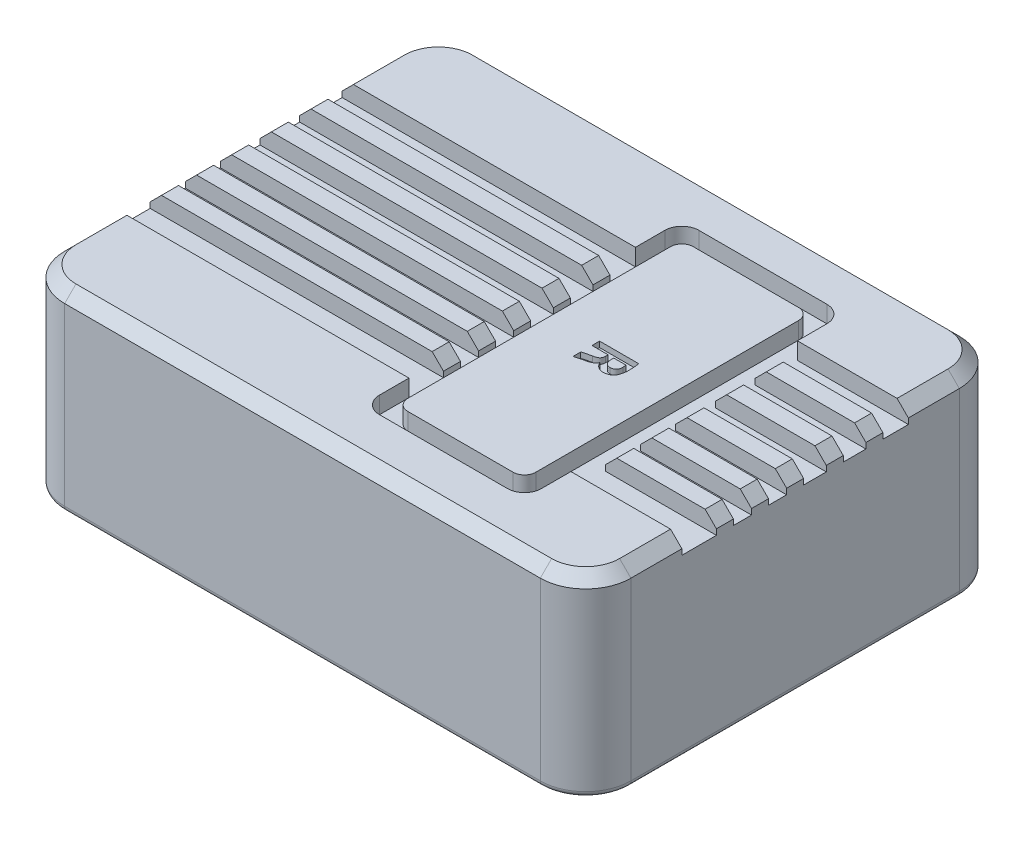
SolidWorks part; units mm, degrees
material "尼龙 101"
ref_plane "前视基准面" through (0, 0, 0) normal (0, 0, 1) x (1, 0, 0)
ref_plane "上视基准面" through (0, 0, 0) normal (0, 1, 0) x (1, 0, 0)
ref_plane "右视基准面" through (0, 0, 0) normal (1, 0, 0) x (0, 0, -1)
sketch "草图1" plane through (0, 0, 0) normal (0, 1, 0) x (1, 0, 0)
  line L1 (-21, 18.5) -> (21, 18.5)
  line L2 (-25, 14.5) -> (-25, -14.5)
  line L3 (-21, -18.5) -> (21, -18.5)
  line L4 (25, 14.5) -> (25, -14.5)
  line L5 (-25, 18.5) -> (25, -18.5) construction
  line L6 (-25, -18.5) -> (25, 18.5) construction
  arc A0 (-21, 18.5) -> (-25, 14.5) centre (-21, 14.5) ccw
  arc A1 (-25, -14.5) -> (-21, -18.5) centre (-21, -14.5) ccw
  arc A2 (21, -18.5) -> (25, -14.5) centre (21, -14.5) ccw
  arc A3 (21, 18.5) -> (25, 14.5) centre (21, 14.5) cw
  point P0 (0, 0)
  dimension "D3" = 4
  dimension "D1" = 50
  dimension "D2" = 37
extrude "凸台-拉伸1" add sketch "草图1" along normal blind 17
sketch "草图3" plane through (0, 17, 0) normal (0, 1, 0) x (1, 0, 0)
  line L0 (25, -14.5) -> (25, 14.5) construction
  line L1 (2.4, 14.1) -> (13.7, 14.1)
  line L2 (0.9, 12.6) -> (0.9, -12.6)
  line L3 (2.4, -14.1) -> (13.7, -14.1)
  line L4 (15.2, 12.6) -> (15.2, -12.6)
  line L5 (0.9, 14.1) -> (15.2, -14.1) construction
  line L6 (0.9, -14.1) -> (15.2, 14.1) construction
  line L7 (0, 0) -> (8.05, 0) construction
  line L9 (-25, 10) -> (25, 10)
  line L10 (-25, 10) -> (-25, -10)
  line L11 (-25, -10) -> (25, -10)
  line L12 (25, 10) -> (25, -10)
  line L13 (-25, 10) -> (25, -10) construction
  line L14 (-25, -10) -> (25, 10) construction
  arc A0 (0.9, -12.6) -> (2.4, -14.1) centre (2.4, -12.6) ccw
  arc A1 (13.7, -14.1) -> (15.2, -12.6) centre (13.7, -12.6) ccw
  arc A2 (13.7, 14.1) -> (15.2, 12.6) centre (13.7, 12.6) cw
  arc A3 (2.4, 14.1) -> (0.9, 12.6) centre (2.4, 12.6) ccw
  point P0 (8.05, 0)
  line M12 (-25, 14.5) -> (-25, -14.5)
  line M16 (25, -14.5) -> (25, 14.5)
  dimension "D1" = 1.5
  dimension "D2" = 14.3
  dimension "D3" = 9.8
  dimension "D4" = 28.2
  dimension "D5" = 20
extrude "切除-拉伸1" cut sketch "草图3" against normal blind 1.5 contours L4 L11 L9 M16 | L2 L11 L4 L9 | L1 A3 L2 L9 L4 A2 | L3 A1 L4 L11 L2 A0 | L11 L2 L9 M12
sketch "草图4" plane through (0, 15.5, 0) normal (0, 1, 0) x (1, 0, 0)
  line L0 (25, -10) -> (25, 10) construction
  line L1 (-25, 0.75) -> (25, 0.75)
  line L2 (-25, 0.75) -> (-25, -0.75)
  line L3 (-25, -0.75) -> (25, -0.75)
  line L4 (25, 0.75) -> (25, -0.75)
  line L5 (-25, 0.75) -> (25, -0.75) construction
  line L6 (-25, -0.75) -> (25, 0.75) construction
  line L7 (-25, 4.25) -> (-25, 2.75)
  line L8 (-25, 4.25) -> (25, 4.25)
  line L9 (25, 4.25) -> (25, 2.75)
  line L10 (-25, 2.75) -> (25, 2.75)
  line L11 (-25, 7.75) -> (-25, 6.25)
  line L12 (-25, 7.75) -> (25, 7.75)
  line L13 (25, 7.75) -> (25, 6.25)
  line L14 (-25, 6.25) -> (25, 6.25)
  line L15 (-25, -2.35) -> (-25, -3.85)
  line L16 (-25, -2.35) -> (25, -2.35)
  line L17 (25, -2.35) -> (25, -3.85)
  line L18 (-25, -3.85) -> (25, -3.85)
  line L19 (-25, -5.45) -> (-25, -6.95)
  line L20 (-25, -5.45) -> (25, -5.45)
  line L21 (25, -5.45) -> (25, -6.95)
  line L22 (-25, -6.95) -> (25, -6.95)
  point P0 (0, 0)
  dimension "D1" = 1.5
  dimension "D2" = 3
  dimension "D3" = 3
extrude "凸台-拉伸2" add sketch "草图4" along normal blind 1.5
sketch "草图5" plane through (0, 17, 0) normal (0, 1, 0) x (1, 0, 0)
  line L0 (8.05, 0) -> (0, 0) construction
  line L1 (3.4, 12.6) -> (12.7, 12.6)
  line L2 (2.4, 11.6) -> (2.4, -11.6)
  line L3 (3.4, -12.6) -> (12.7, -12.6)
  line L4 (13.7, 11.6) -> (13.7, -11.6)
  line L5 (2.4, 12.6) -> (13.7, -12.6) construction
  line L6 (2.4, -12.6) -> (13.7, 12.6) construction
  line L7 (15.2, 12.6) -> (15.2, 10) construction
  line L8 (0.9, 12.6) -> (0.9, 10) construction
  line L9 (2.4, 14.1) -> (13.7, 14.1) construction
  arc A0 (12.7, -12.6) -> (13.7, -11.6) centre (12.7, -11.6) ccw
  arc A1 (2.4, -11.6) -> (3.4, -12.6) centre (3.4, -11.6) ccw
  arc A2 (3.4, 12.6) -> (2.4, 11.6) centre (3.4, 11.6) ccw
  arc A3 (12.7, 12.6) -> (13.7, 11.6) centre (12.7, 11.6) cw
  point P0 (8.05, 0)
  dimension "D1" = 1
  dimension "D2" = 1.5
  dimension "D3" = 1.5
  dimension "D4" = 1.5
extrude "凸台-拉伸3" add sketch "草图5" against normal blind 9.5
sketch "草图6" plane through (0, 17, 0) normal (0, 1, 0) x (1, 0, 0)
  line L0 (13.7, -11.6) -> (13.7, -6.95) construction
  line L1 (3.4, -12.6) -> (12.7, -12.6) construction
  line L2 (2.4, -6.95) -> (2.4, -11.6) construction
  line L3 (2.4, 11.6) -> (2.4, 7.75) construction
  line L4 (12.7, 12.6) -> (3.4, 12.6) construction
  line L5 (13.7, 7.75) -> (13.7, 11.6) construction
  line L6 (13.7, -11.6) -> (13.7, -6.95)
  line L7 (3.4, -12.6) -> (12.7, -12.6)
  line L8 (2.4, -6.95) -> (2.4, -11.6)
  line L9 (2.4, 11.6) -> (2.4, 7.75)
  line L10 (12.7, 12.6) -> (3.4, 12.6)
  line L11 (13.7, 7.75) -> (13.7, 11.6)
  line L12 (15.2, -10) -> (15.2, -12.6) construction
  line L13 (2.4, -14.1) -> (13.7, -14.1) construction
  line L14 (0.9, -10) -> (0.9, -12.6) construction
  line L15 (0.9, 12.6) -> (0.9, 10) construction
  line L16 (2.4, 14.1) -> (13.7, 14.1) construction
  line L17 (15.2, 12.6) -> (15.2, 10) construction
  line L18 (15.2, -10) -> (15.2, -12.6)
  line L19 (2.4, -14.1) -> (13.7, -14.1)
  line L20 (0.9, -10) -> (0.9, -12.6)
  line L21 (0.9, 12.6) -> (0.9, 10)
  line L22 (2.4, 14.1) -> (13.7, 14.1)
  line L23 (15.2, 12.6) -> (15.2, 10)
  line L24 (13.7, 7.75) -> (13.7, -6.95)
  line L25 (15.2, 10) -> (15.2, -10)
  line L26 (0.9, 10) -> (0.9, -10)
  line L27 (2.4, 7.75) -> (2.4, -6.95)
  arc A0 (12.7, -12.6) -> (13.7, -11.6) centre (12.7, -11.6) ccw construction
  arc A1 (2.4, -11.6) -> (3.4, -12.6) centre (3.4, -11.6) ccw construction
  arc A2 (3.4, 12.6) -> (2.4, 11.6) centre (3.4, 11.6) ccw construction
  arc A3 (13.7, 11.6) -> (12.7, 12.6) centre (12.7, 11.6) ccw construction
  arc A4 (12.7, -12.6) -> (13.7, -11.6) centre (12.7, -11.6) ccw
  arc A5 (2.4, -11.6) -> (3.4, -12.6) centre (3.4, -11.6) ccw
  arc A6 (3.4, 12.6) -> (2.4, 11.6) centre (3.4, 11.6) ccw
  arc A7 (13.7, 11.6) -> (12.7, 12.6) centre (12.7, 11.6) ccw
  arc A8 (13.7, -14.1) -> (15.2, -12.6) centre (13.7, -12.6) ccw construction
  arc A9 (0.9, -12.6) -> (2.4, -14.1) centre (2.4, -12.6) ccw construction
  arc A10 (2.4, 14.1) -> (0.9, 12.6) centre (2.4, 12.6) ccw construction
  arc A11 (15.2, 12.6) -> (13.7, 14.1) centre (13.7, 12.6) ccw construction
  arc A12 (13.7, -14.1) -> (15.2, -12.6) centre (13.7, -12.6) ccw
  arc A13 (0.9, -12.6) -> (2.4, -14.1) centre (2.4, -12.6) ccw
  arc A14 (2.4, 14.1) -> (0.9, 12.6) centre (2.4, 12.6) ccw
  arc A15 (15.2, 12.6) -> (13.7, 14.1) centre (13.7, 12.6) ccw
extrude "切除-拉伸2" cut sketch "草图6" against normal blind 1.5
chamfer "倒角1" distance 1 angle 45 28 edges at (0.9, 17, 6.2) (0.9, 17, 3.1) (0.9, 17, 0) (0.9, 17, -3.5) (0.9, 17, -7) (15.2, 17, 6.2) (15.2, 17, 3.1) (15.2, 17, 0) (15.2, 17, -3.5) (25, 17, -3.5) (25, 17, 0) (25, 17, 3.1) (25, 17, 6.2) (-25, 17, 6.2) (-25, 17, 3.1) (-25, 17, 0) (-25, 17, -3.5) (-25, 17, -7) (25, 17, -12.25) (23.8284, 17, -17.3284) (0, 17, -18.5) (-23.8284, 17, -17.3284) (-25, 17, -12.25) (-25, 17, 12.25) (25, 17, 12.25) (-23.8284, 17, 17.3284) (23.8284, 17, 17.3284) (0, 17, 18.5)
fillet "圆角1" radius 0.5 8 edges at (23.8284, 0, -17.3284) (25, 0, 0) (23.8284, 0, 17.3284) (0, 0, 18.5) (-23.8284, 0, 17.3284) (-25, 0, 0) (-23.8284, 0, -17.3284) (0, 0, -18.5)
sketch "草图7" plane through (0, 0, 0) normal (0, -1, 0) x (1, 0, 0)
  line L0 (-21, 14.5) -> (-21, -14.5) construction
  line L1 (0, 0) -> (-21, 0) construction
  line L2 (-25, -14.5) -> (-25, 14.5) construction
  line L3 (25, 14.5) -> (25, -14.5) construction
  circle A0 centre (21.5, 0) radius 1
  circle A1 centre (-21, 14.5) radius 1
  circle A2 centre (-21, -14.5) radius 1
  dimension "D1" = 2
  dimension "D2" = 29
  dimension "D3" = 4
  dimension "D4" = 3.5
extrude "切除-拉伸3" cut sketch "草图7" against normal blind 5
chamfer "倒角2" distance 0.5 angle 45 3 edges at (-21, 0, 13.5) (-21, 0, -15.5) (21.5, 0, -1)
sketch "草图8" plane through (0, 17, 0) normal (0, 1, 0) x (1, 0, 0)
  text T0 "<r270>R</r>" font "@Adobe Gothic Std B" height 3.5
  point P1 (7.2037, 1.7046)
  point P2 (6.35, 0.8804)
  point P3 (6.9844, 1.5594)
  point P4 (6.4737, 1.5852)
extrude "切除-拉伸4" cut sketch "草图8" against normal blind 0.5
